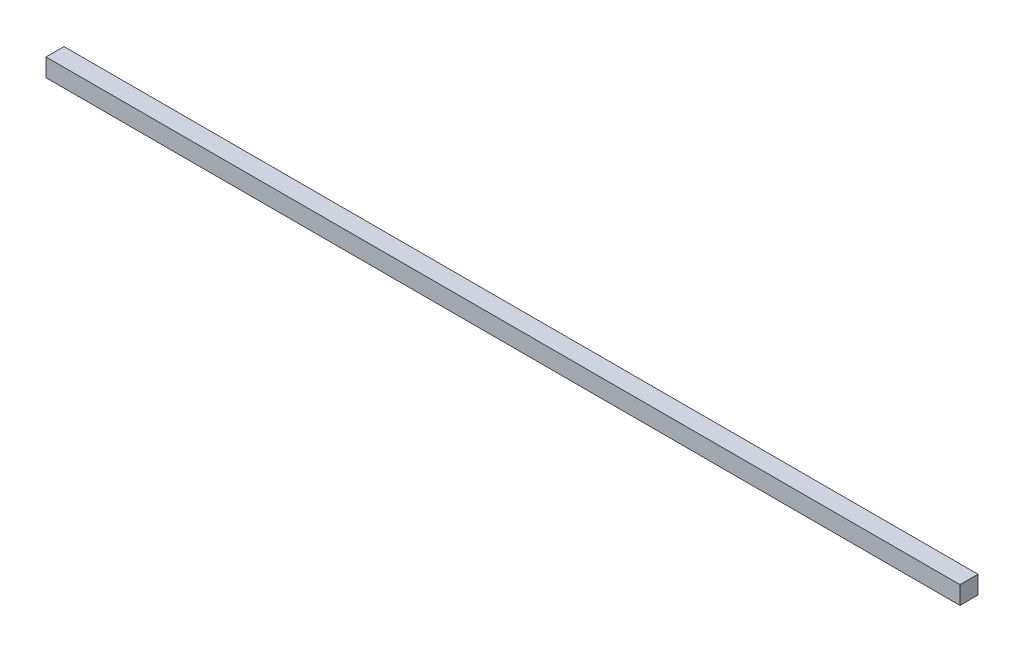
SolidWorks part; units mm, degrees
ref_plane "Спереди" through (0, 0, 0) normal (0, 0, 1) x (1, 0, 0)
ref_plane "Сверху" through (0, 0, 0) normal (0, 1, 0) x (1, 0, 0)
ref_plane "Справа" through (0, 0, 0) normal (1, 0, 0) x (0, 0, -1)
other "Configuration Table"
sketch "Эскиз1" plane through (0, 0, 0) normal (1, 0, 0) x (0, 0, -1)
  line L1 (0, 0) -> (6, 0)
  line L2 (0, 0) -> (0, 6)
  line L3 (0, 6) -> (6, 6)
  line L4 (6, 0) -> (6, 6)
extrude "Бобышка-Вытянуть1" add sketch "Эскиз1" along normal blind 304.5
